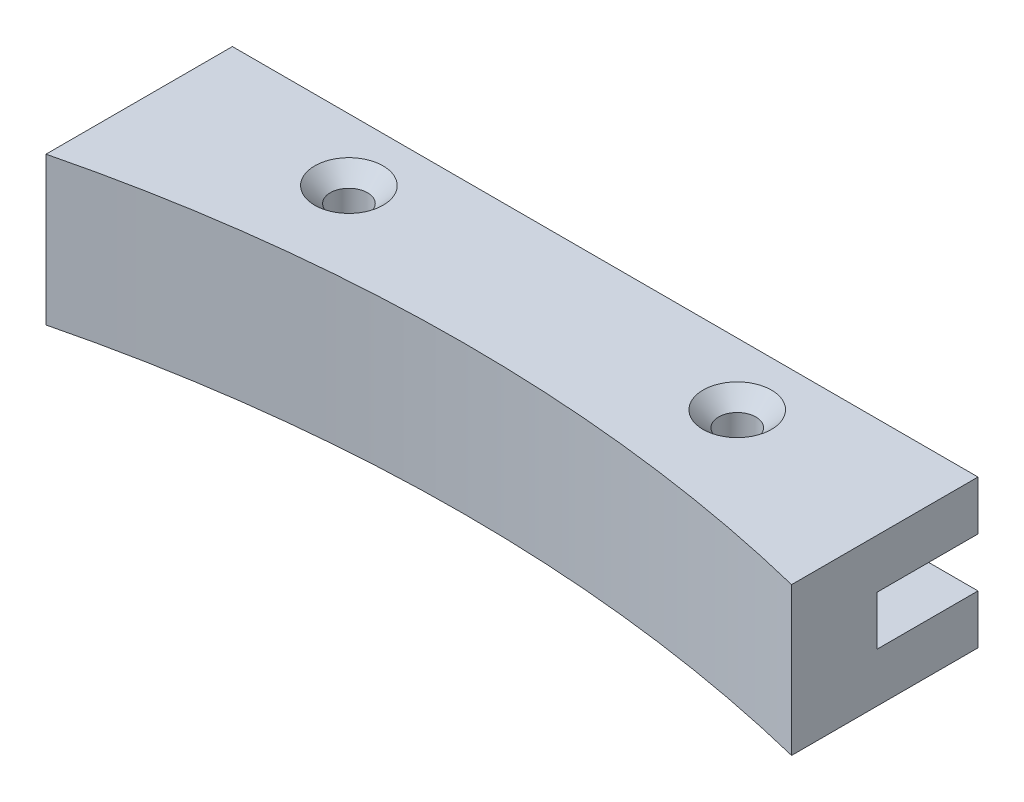
SolidWorks part; units mm, degrees
material "6061-T6 (SS)"
ref_plane "Front Plane" through (0, 0, 0) normal (0, 0, 1) x (1, 0, 0)
ref_plane "Top Plane" through (0, 0, 0) normal (0, 1, 0) x (1, 0, 0)
ref_plane "Right Plane" through (0, 0, 0) normal (1, 0, 0) x (0, 0, -1)
sketch "Sketch1" plane through (0, 0, 0) normal (0, 1, 0) x (1, 0, 0)
  line L0 (-24, 0) -> (24, 0)
  line L1 (24, 0) -> (24, -12)
  line L2 (-24, 0) -> (-24, -12)
  line L3 (-24, -9.0773) -> (24, -9.0773) construction
  line L25 (-24, -12) -> (0, -109.0773) construction
  line L26 (0, -109.0773) -> (24, -12) construction
  arc A0 (-24, -12) -> (24, -12) centre (0, -109.0773) cw
  point P0 (0, 0)
  dimension "D1" = 12
  dimension "D2" = 100
  dimension "D5" = 48
extrude "Boss-Extrude1" add sketch "Sketch1" along normal mid plane 9.525
sketch "Sketch9" plane through (-24, 0, 0) normal (-1, 0, 0) x (0, 0, 1)
  line L0 (0, 4.7625) -> (0, -4.7625) construction
  line L1 (0, -1.5875) -> (6.5, -1.5875)
  line L2 (0, -1.5875) -> (0, 1.5875)
  line L3 (0, 1.5875) -> (6.5, 1.5875)
  line L4 (6.5, -1.5875) -> (6.5, 1.5875)
  point P6 (0, 0)
  dimension "D1" = 3.175
  dimension "D2" = 6.5
extrude "Cut-Extrude2" cut sketch "Sketch9" against normal through all
sketch "Sketch10" plane through (0, 4.7625, 0) normal (0, 1, 0) x (1, 0, 0)
  line L0 (24, 0) -> (-24, 0) construction
  point P0 (-12.5, -4)
  point P1 (12.5, -4)
  point P5 (-13.4578, -3.4684)
  point P6 (0, 0)
  dimension "D1" = 12.5
  dimension "D2" = 4
  dimension "D3" = 25
hole_wizard "CSK for M2 Flat Head Machine Screw1" positions "Sketch13" profile "Sketch14" countersink size "M2" standard "ANSI Metric"
sketch "Sketch13" plane through (0, 4.7625, 0) normal (0, 1, 0) x (1, 0, 0)
  point P0 (-12.5, -4)
  point P3 (12.5, -4)
sketch "Sketch14" plane through (-12.5, 4.7625, 4) normal (1, 0, 0) x (0, 0, 1)
  line L0 (0, 0) -> (0, 3.175)
  line L1 (0, 3.175) -> (1.2, 3.175)
  line L2 (1.2, 3.175) -> (1.2, 1)
  line L3 (1.2, 1) -> (2.2, 0)
  line L5 (2.2, 0) -> (0, 0)
  line L6 (-1.2, 1) -> (-2.2, 0) construction
  line L11 (0, -6.35) -> (0, 107.95) construction
  dimension "Thru Hole Dia." = 2.4
  dimension "Thru Hole Depth" = 3.175
  dimension "Near C'Sink Dia." = 4.4
  dimension "Near C'Sink Angle" = 90
hole_wizard "M2x0.4 Tapped Hole1" positions "Sketch15" profile "Sketch17" tap size "M2x0.4" standard "ANSI Metric" end condition up to next
sketch "Sketch15" plane through (0, -1.5875, 0) normal (0, 1, 0) x (1, 0, 0)
  point P0 (-12.5, -4)
  point P3 (12.5, -4)
sketch "Sketch17" plane through (-12.5, -1.5875, 4) normal (1, 0, 0) x (0, 0, 1)
  line L0 (0, 0) -> (0, 3.175)
  line L1 (0, 3.175) -> (0.8, 3.175)
  line L2 (0.8, 3.175) -> (0.8, 0)
  line L5 (0.8, 0) -> (0, 0)
  line L11 (0, -6.35) -> (0, 107.95) construction
  dimension "Thru Tap Drill Dia." = 1.6
  dimension "Thru Tap Drill Depth" = 3.175
cosmetic thread "Hole Thread1" parameters "D2"=2
cosmetic thread "Hole Thread2" parameters "D2"=2
